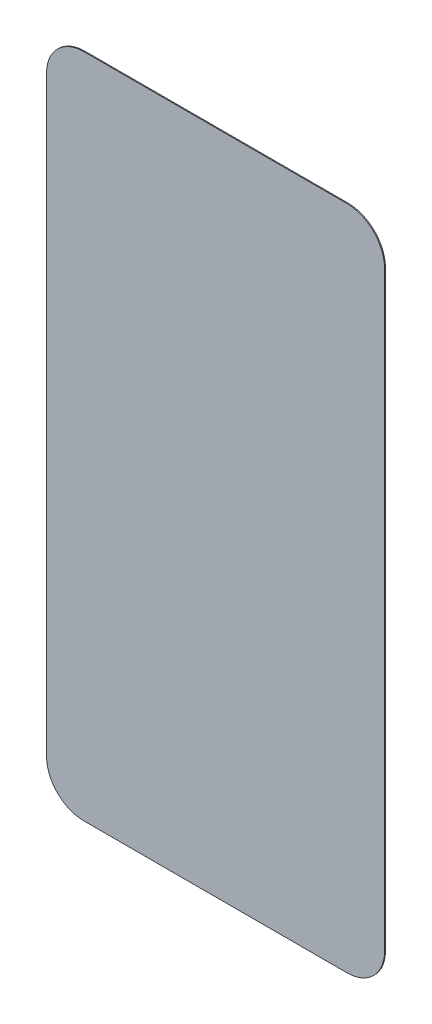
SolidWorks part; units mm, degrees
material "AISI 316 Нержавеющая сталь, лист (SS)"
ref_plane "Спереди" through (0, 0, 0) normal (0, 0, 1) x (1, 0, 0)
ref_plane "Сверху" through (0, 0, 0) normal (0, 1, 0) x (1, 0, 0)
ref_plane "Справа" through (0, 0, 0) normal (1, 0, 0) x (0, 0, -1)
sketch "Эскиз1" plane through (0, 0, 0) normal (0, 0, 1) x (1, 0, 0)
  line L0 (85.5687, 21.1894) -> (85.5687, 37.5182) construction
  line L1 (15.0687, 21.1894) -> (156.0687, 21.1894)
  line L2 (-4.9313, 1.1894) -> (-4.9313, -315.5717)
  line L3 (15.0687, -335.5717) -> (156.0687, -335.5717)
  line L4 (176.0687, 1.1894) -> (176.0687, -315.5717)
  arc A0 (15.0687, 21.1894) -> (-4.9313, 1.1894) centre (15.0687, 1.1894) ccw
  arc A1 (176.0687, 1.1894) -> (156.0687, 21.1894) centre (156.0687, 1.1894) ccw
  arc A2 (156.0687, -335.5717) -> (176.0687, -315.5717) centre (156.0687, -315.5717) ccw
  arc A3 (-4.9313, -315.5717) -> (15.0687, -335.5717) centre (15.0687, -315.5717) ccw
  dimension "D1" = 20
extrude "Вытянуть1" add sketch "Эскиз1" along normal blind 0.5
